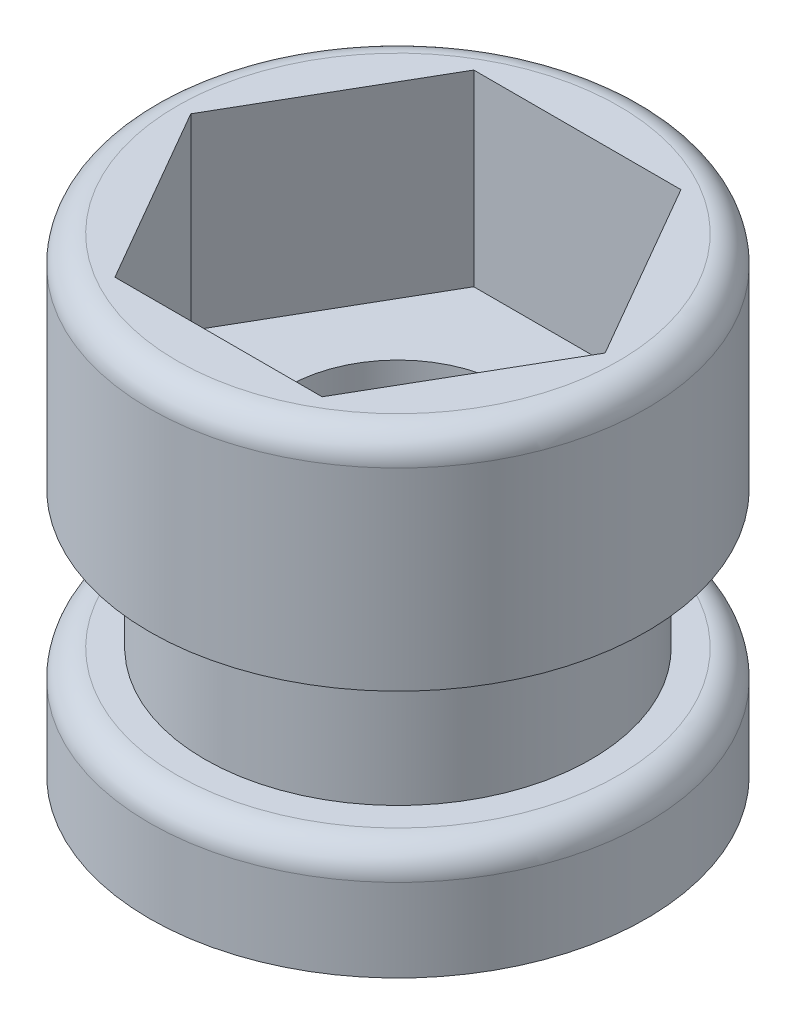
SolidWorks part; units mm, degrees
ref_plane "Front Plane" through (0, 0, 0) normal (0, 0, 1) x (1, 0, 0)
ref_plane "Top Plane" through (0, 0, 0) normal (0, 1, 0) x (1, 0, 0)
ref_plane "Right Plane" through (0, 0, 0) normal (1, 0, 0) x (0, 0, -1)
sketch "Sketch1" plane through (0, 0, 0) normal (0, 1, 0) x (1, 0, 0)
  circle A0 centre (0, 0) radius 9
extrude "Boss-Extrude1" add sketch "Sketch1" along normal blind 4
sketch "Sketch2" plane through (0, 4, 0) normal (0, 1, 0) x (1, 0, 0)
  circle A0 centre (0, 0) radius 7
extrude "Boss-Extrude2" add sketch "Sketch2" along normal blind 5
sketch "Sketch4" plane through (0, 9, 0) normal (0, 1, 0) x (1, 0, 0)
  circle A0 centre (0, 0) radius 9
extrude "Boss-Extrude3" add sketch "Sketch4" along normal blind 8
fillet "Fillet1" radius 1 1 edges at (0, 17, 9)
fillet "Fillet2" radius 1 1 edges at (0, 4, 9)
sketch "Sketch5" plane through (0, 0, 0) normal (0, -1, 0) x (1, 0, 0)
  circle A0 centre (0, 0) radius 4
extrude "Cut-Extrude1" cut sketch "Sketch5" against normal blind 18
sketch "Sketch6" plane through (0, 17, 0) normal (0, 1, 0) x (1, 0, 0)
  line L1 (-7.5056, 0) -> (-3.7528, -6.5)
  line L2 (-3.7528, -6.5) -> (3.7528, -6.5)
  line L3 (3.7528, -6.5) -> (7.5056, 0)
  line L4 (7.5056, 0) -> (3.7528, 6.5)
  line L5 (3.7528, 6.5) -> (-3.7528, 6.5)
  line L6 (-3.7528, 6.5) -> (-7.5056, 0)
  circle A0 centre (0, 0) radius 6.5 construction
extrude "Cut-Extrude2" cut sketch "Sketch6" against normal blind 6.8
